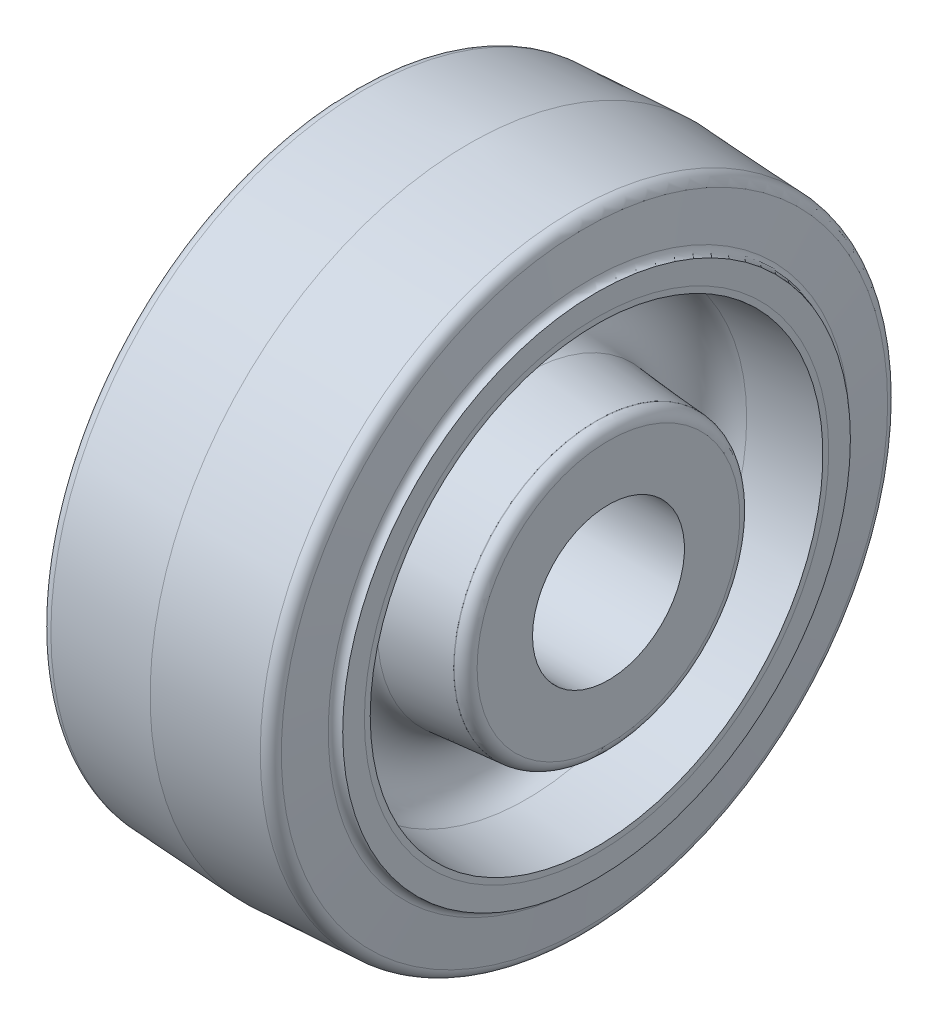
SolidWorks part; units mm, degrees
ref_plane "Front Plane" through (0, 0, 0) normal (0, 0, 1) x (1, 0, 0)
ref_plane "Top Plane" through (0, 0, 0) normal (0, 1, 0) x (1, 0, 0)
ref_plane "Right Plane" through (0, 0, 0) normal (1, 0, 0) x (0, 0, -1)
sketch "Sketch4" plane through (0, 0, 0) normal (0, 0, 1) x (1, 0, 0)
  line L0 (25.4, 46.228) -> (25.4, 50.546)
  line L1 (23.8843, 51.9107) -> (22.9959, 60.3638)
  line L2 (20.8421, 62.4077) -> (0, 63.5)
  line L3 (0, 63.5) -> (-20.8421, 62.4077)
  line L4 (-22.9959, 60.3638) -> (-23.8843, 51.9107)
  line L5 (-25.4, 50.546) -> (-25.4, 46.228)
  line L6 (-25.4, 46.228) -> (-19.05, 46.228)
  line L7 (-19.05, 46.228) -> (-19.05, 53.848)
  line L8 (-19.05, 53.848) -> (19.05, 53.848)
  line L9 (19.05, 53.848) -> (19.05, 46.228)
  line L10 (19.05, 46.228) -> (25.4, 46.228)
  line L11 (-25.4, 0) -> (25.4, 0) construction
  arc A0 (25.4, 50.546) -> (23.8843, 51.9107) centre (25.4, 52.07) cw
  arc A1 (22.9959, 60.3638) -> (20.8421, 62.4077) centre (20.7224, 60.1248) ccw
  arc A2 (-20.8421, 62.4077) -> (-22.9959, 60.3638) centre (-20.7224, 60.1248) ccw
  arc A3 (-23.8843, 51.9107) -> (-25.4, 50.546) centre (-25.4, 52.07) cw
revolve "Revolve3" add sketch "Sketch4" angle 360 about L11
ref_plane "Plane2" through (0, 0, 0) normal (0, 0, -1) x (-1, 0, 0)
sketch "Sketch8" plane through (0, 0, 0) normal (0, 0, -1) x (-1, 0, 0)
  line L0 (-27.7749, 15.1257) -> (27.7749, 15.1257)
  line L1 (27.7749, 15.1257) -> (27.7749, 26.162)
  line L2 (25.4889, 28.448) -> (25.4, 28.448)
  line L3 (25.4, 28.448) -> (25.4, 28.4558)
  line L4 (25.4, 28.4558) -> (11.4451, 29.6767)
  line L5 (11.4451, 43.8465) -> (25.4, 45.0674)
  line L6 (25.4, 45.0674) -> (25.4, 46.228)
  line L7 (25.4, 46.228) -> (19.05, 46.228)
  line L8 (19.05, 46.228) -> (19.05, 53.848)
  line L9 (19.05, 53.848) -> (-19.05, 53.848)
  line L10 (-19.05, 53.848) -> (-19.05, 46.228)
  line L11 (-19.05, 46.228) -> (-25.4, 46.228)
  line L12 (-25.4, 46.228) -> (-25.4, 45.0674)
  line L13 (-25.4, 45.0674) -> (-11.4451, 43.8465)
  line L14 (-11.4451, 29.6767) -> (-25.4, 28.4558)
  line L15 (-25.4, 28.4558) -> (-25.4, 28.448)
  line L16 (-25.4, 28.448) -> (-25.4889, 28.448)
  line L17 (-27.7749, 26.162) -> (-27.7749, 15.1257)
  line L18 (-27.7749, 0) -> (27.7749, 0) construction
  arc A0 (27.7749, 26.162) -> (25.4889, 28.448) centre (25.4889, 26.162) ccw
  arc A1 (11.4451, 29.6767) -> (11.4451, 43.8465) centre (12.065, 36.7616) cw
  arc A2 (-11.4451, 43.8465) -> (-11.4451, 29.6767) centre (-12.065, 36.7616) cw
  arc A3 (-25.4889, 28.448) -> (-27.7749, 26.162) centre (-25.4889, 26.162) ccw
revolve "Revolve4" add sketch "Sketch8" angle 360 about L18
sketch "Sketch9" plane through (0, 0, 0) normal (1, 0, 0) x (0, 0, -1)
  circle A0 centre (0, 0) radius 63.5 construction
  circle A1 centre (0, 0) radius 63.5
  point P3 (0, -63.5)
